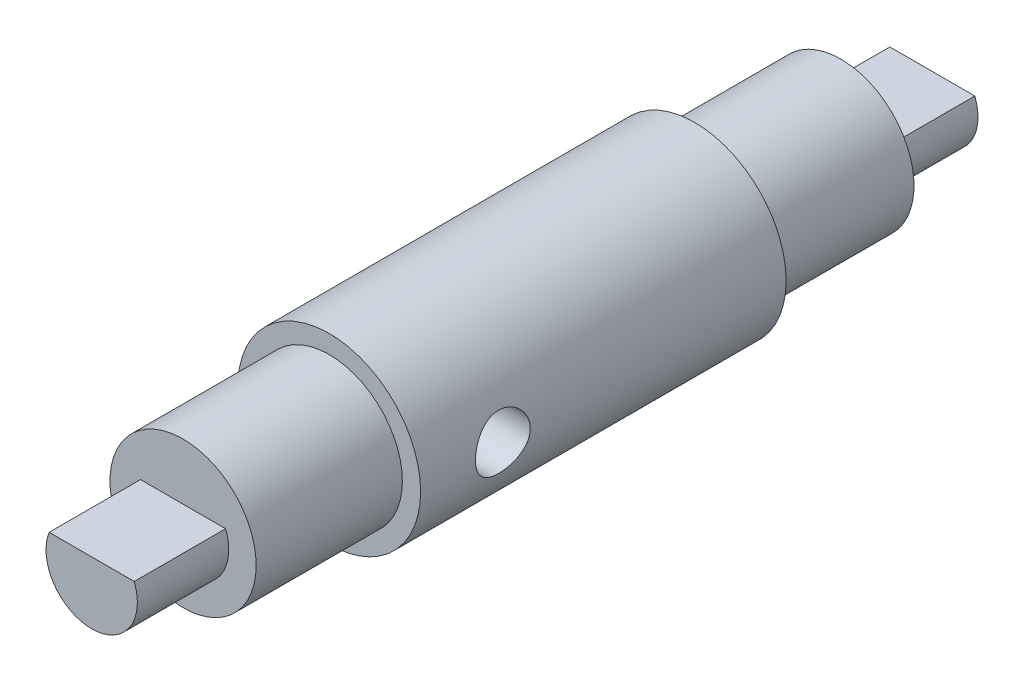
SolidWorks part; units mm, degrees
material "Cast Alloy Steel"
ref_plane "Front Plane" through (0, 0, 0) normal (0, 0, 1) x (1, 0, 0)
ref_plane "Top Plane" through (0, 0, 0) normal (0, 1, 0) x (1, 0, 0)
ref_plane "Right Plane" through (0, 0, 0) normal (1, 0, 0) x (0, 0, -1)
sketch "Sketch1" plane through (0, 0, 0) normal (0, 0, 1) x (1, 0, 0)
  circle A0 centre (0, 0) radius 5
  dimension "D1" = 10
extrude "Boss-Extrude1" add sketch "Sketch1" along normal blind 20
sketch "Sketch2" plane through (0, 0, 20) normal (0, 0, 1) x (1, 0, 0)
  circle A0 centre (0, 0) radius 3.5
  dimension "D1" = 7
extrude "Boss-Extrude2" add sketch "Sketch2" along normal blind 8
sketch "Sketch3" plane through (0, 0, 0) normal (0, 0, -1) x (-1, 0, 0)
  circle A0 centre (0, 0) radius 3.5
  dimension "D1" = 7
extrude "Boss-Extrude3" add sketch "Sketch3" along normal blind 8
sketch "Sketch4" plane through (0, 0, -8) normal (0, 0, -1) x (-1, 0, 0)
  line L0 (-2.3269, 0.914) -> (2.3269, 0.914)
  circle A0 centre (0, 0) radius 2.5
  dimension "D1" = 5
extrude "Boss-Extrude4" add sketch "Sketch4" along normal blind 5 contours L0 A0
sketch "Sketch5" plane through (0, 0, 28) normal (0, 0, 1) x (1, 0, 0)
  circle A0 centre (0, 0) radius 2.5
  dimension "D1" = 5
sketch "Sketch6" plane through (0, 0, 28) normal (0, 0, 1) x (1, 0, 0)
  line L0 (-2.3285, 0.91) -> (2.3285, 0.91)
  circle A0 centre (0, 0) radius 2.5 construction
  circle A1 centre (0, 0) radius 2.5
  dimension "D2" = 5
  dimension "D1" = 0.91
extrude "Boss-Extrude5" add sketch "Sketch6" along normal blind 5 contours L0 A1
ref_plane "Plane1" through (-5, 0, 0) normal (-1, 0, 0) x (0, 0, 1)
sketch "Sketch7" plane through (-5, 0, 0) normal (-1, 0, 0) x (0, 0, 1)
  line L0 (20, -3.5) -> (20, 3.5) construction
  circle A0 centre (15.5, 0) radius 1.5
  dimension "D2" = 3
  dimension "D1" = 4.5
extrude "Cut-Extrude1" cut sketch "Sketch7" against normal blind 15
sketch "Sketch8" plane through (0, 0, -8) normal (0, 0, -1) x (-1, 0, 0)
  circle A2 centre (0, 0) radius 4
  dimension "D1" = 8
extrude "Boss-Extrude6" add sketch "Sketch8" against normal up to next
sketch "Sketch9" plane through (0, 0, 28) normal (0, 0, 1) x (1, 0, 0)
  circle A0 centre (0, 0) radius 4
  dimension "D1" = 8
extrude "Boss-Extrude7" add sketch "Sketch9" against normal up to next
